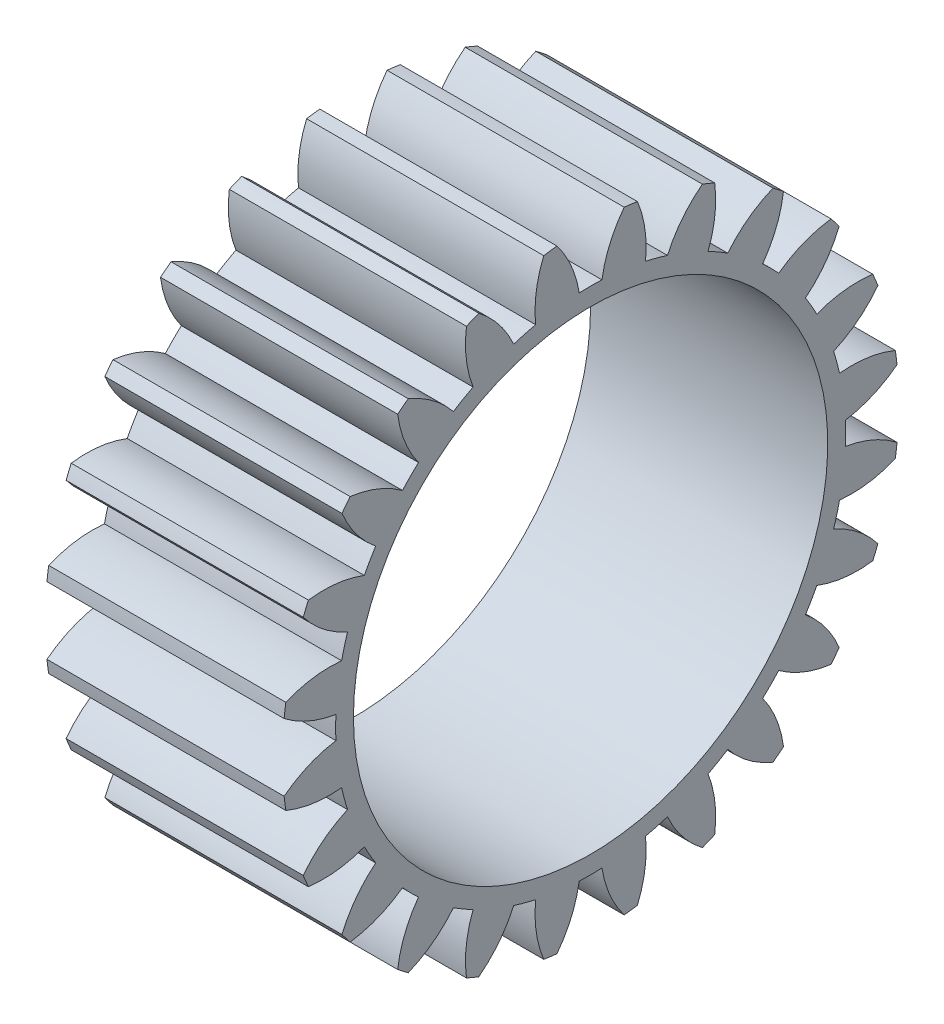
SolidWorks part; units mm, degrees
ref_plane "Plane1" through (0, 0, 0) normal (0, 0, 1) x (1, 0, 0)
ref_plane "Plane2" through (0, 0, 0) normal (0, 1, 0) x (1, 0, 0)
ref_plane "Plane3" through (0, 0, 0) normal (1, 0, 0) x (0, 0, -1)
sketch "HoldingSke" plane through (0, 0, 0) normal (0, 1, 0) x (1, 0, 0)
  line L0 (0, 0) -> (0.609, -0.2712)
  line L1 (-15, 0) -> (100, 0) construction
  line L2 (0, 0) -> (-2.1039, 2.3779)
  line L3 (0, 0) -> (-11.863, 4.5341)
  line L4 (0, 0) -> (7.8894, 3.5126)
  line L5 (0, 0) -> (-46.8476, -17.4728)
  line L6 (0, 0) -> (-12.4344, -8.3896)
  line L7 (-2.1039, 2.3779) -> (8.6586, 51.2059)
  line L8 (-76.2, 54.61) -> (-72.9, 54.61)
  line L9 (-71.009, 38.7566) -> (-53.1078, 45.2721)
  line L10 (-76.2, 71.12) -> (104.1128, 71.12)
  line L11 (0, 0) -> (-15, 0)
  line L12 (-76.2, 101.6) -> (-76.147, 101.6)
  line L13 (24.9733, 27.94) -> (52.9518, 28.4284)
  line L14 (24.9733, 27.94) -> (24.9743, 27.94)
  line L15 (24.9733, 27.94) -> (100.4006, 29.5858)
  line L16 (-63.627, -1.5) -> (-12.827, -1.5)
  circle A0 centre (0, 0) radius 15
  circle A1 centre (0, 0) radius 16.124
  circle A2 centre (0, 0) radius 37.5
  circle A3 centre (0, 0) radius 15
  dimension "MHD" = 32.248
  dimension "Hub_dia" = 75
  dimension "Bore" = 30
  dimension "MBD" = 30
  dimension "Num_teeth" = 24
  dimension "Pitch" = 0.6667
  dimension "Overall_len" = 50
  dimension "Show_teeth" = 24
  dimension "Thickness" = 15
  dimension "OAL" = 50.0001
  dimension "T_dim" = 3.3
  dimension "Ap" = 20
  dimension "H" = 19.05
  dimension "Pitch_radius" = 180.3128
  dimension "Width" = 15
  dimension "Backlash" = 0.053
  dimension "Addendum_fac" = 1
  dimension "Dedendum_fac" = 1.25
  dimension "Clearance_fac" = 0.25
  dimension "Dedendum_add" = 0.001
  dimension "Module" = 1.5
sketch "BasProSke" plane through (0, 0, 0) normal (0, 1, 0) x (1, 0, 0)
  line L0 (-10, 0) -> (60, 0) construction
  line L1 (0, 0) -> (0, 19.5)
  line L2 (0, 0) -> (15, 0)
  line L3 (15, 0) -> (15, 19.5)
  line L4 (15, 19.5) -> (0, 19.5)
  dimension "Thickness" = 15
  dimension "Diameter" = 39
revolve "Base-Revolve" add sketch "BasProSke" angle 360 about L0
sketch "TooCutSke" plane through (0, 0, 0) normal (1, 0, 0) x (0, 0, -1)
  line L1 (0, 0) -> (0, 107) construction
  line L2 (0, 0) -> (-1.27, 17.9551) construction
  line L3 (0, 0) -> (-4.6904, 35.6272) construction
  line L4 (-1.27, 17.9551) -> (-2.3452, 17.8136) construction
  arc A0 (0.719, 16.108) -> (-0.719, 16.108) centre (0, 0) ccw
  arc A1 (2.1447, 19.4073) -> (-2.1447, 19.4073) centre (0, 0) ccw
  circle A2 centre (0, 0) radius 18 construction
  circle A3 centre (0, 0) radius 16.9145 construction
  arc A4 (-0.719, 16.108) -> (-2.1447, 19.4073) centre (-7.832, 14.992) ccw
  arc A5 (2.1447, 19.4073) -> (0.719, 16.108) centre (7.832, 14.992) ccw
  dimension "Root_dia" = 32.248
  dimension "Overcut_dia" = 39.0508
  dimension "Pitch_dia" = 36
  dimension "Base_dia" = 33.8289
  dimension "Flank_rad" = 7.2
  dimension "Half_ang" = 7.5
  dimension "Half_CT" = 1.0845
extrude "ToothCut" cut sketch "TooCutSke" along normal through all
fillet "Breaks" [suppressed] radius 0.03
fillet "RootFillets" [suppressed] radius 0.376
pattern_circular "TeethCuts" count 24 every 15 about axis through (-10, 0, 0) along (1, 0, 0) of "ToothCut", "RootFillets", "Breaks"
sketch "HubNeaOneSke" plane through (0, 0, 0) normal (-1, 0, 0) x (0, 0, 1)
  circle A0 centre (0, 0) radius 16.124
  dimension "Diameter" = 32.248
extrude "HubNearOne" [suppressed] add sketch "HubNeaOneSke" along normal blind 35.0001
sketch "HubNeaBotSke" plane through (0, 0, 0) normal (-1, 0, 0) x (0, 0, 1)
  circle A0 centre (0, 0) radius 16.124
  dimension "Diameter" = 32.248
extrude "HubNearBoth" [suppressed] add sketch "HubNeaBotSke" along normal blind 17.5
ref_plane "FarPln" through (15, 0, 0) normal (1, 0, 0) x (0, 0, -1)
sketch "HubFarSke" plane through (15, 0, 0) normal (1, 0, 0) x (0, 0, -1)
  circle A0 centre (0, 0) radius 16.124
  dimension "Diameter" = 32.248
extrude "HubFar" [suppressed] add sketch "HubFarSke" along normal blind 17.5
sketch "BorSke" plane through (0, 0, 0) normal (1, 0, 0) x (0, 0, -1)
  circle A0 centre (0, 0) radius 15
  dimension "Diameter" = 30
extrude "Bore" cut sketch "BorSke" along normal mid plane 100.0001
sketch "KeySke" plane through (0, 0, 0) normal (1, 0, 0) x (0, 0, -1)
  line L0 (-5, 0) -> (-5, 18.3)
  line L1 (-5, 18.3) -> (5, 18.3)
  line L2 (5, 18.3) -> (5, 0)
  line L3 (0, 0) -> (0, 34) construction
  line L4 (-5, 0) -> (5, 0)
  dimension "Offset" = 18.3
  dimension "Width" = 10
extrude "Keyway" [suppressed] cut sketch "KeySke" along normal mid plane 100.0001
pattern_circular "Keyway2" [suppressed] count 2 every 90 about axis through (-10, 0, 0) along (1, 0, 0)
equation "' \"Module@HoldingSke\" = 6.35"
equation "' \"Num_teeth@HoldingSke\" = 12"
equation "' \"Ap@HoldingSke\" =  20"
equation "' \"Ap@HoldingSke\" = 20"
equation "' \"Width@HoldingSke\" = 0.5 * 25.4"
equation "' \"Hub_dia@HoldingSke\"= 1 * 25.4"
equation "' \"Hub_dia@HoldingSke\" = 1 * 25.4"
equation "' \"Overall_len@HoldingSke\" = 1.0 * 25.4"
equation "' \"Bore@HoldingSke\" = 0.75 * 25.4"
equation "' \"T_dim@HoldingSke\" = 0.1 * 25.4"
equation "' \"Width@KeySke\" = 0.25 * 25.4"
equation "' \"Show_teeth@HoldingSke\" = 13"
equation "' \"Backlash@HoldingSke\" = 0.009 * 25.4"
equation "' \"Addendum_fac@HoldingSke\" = 1.0"
equation "' \"Dedendum_fac@HoldingSke\" = 1.25"
equation "' \"Dedendum_add@HoldingSke\" = 0.00005 * 25.4"
equation "' \"Clearance_fac@HoldingSke\" = 0.25"
equation "\"Pitch@HoldingSke\" = 1 / \"Module@HoldingSke\""
equation "\"Overcut_dia@TooCutSke\" = (\"Num_teeth@HoldingSke\" + 2 * \"Addendum_fac@HoldingSke\") / \"Pitch@HoldingSke\" + 0.002 * 25.4"
equation "\"Pitch_dia@TooCutSke\" = \"Num_teeth@HoldingSke\" / \"Pitch@HoldingSke\""
equation "\"Base_dia@TooCutSke\" = \"Num_teeth@HoldingSke\" / \"Pitch@HoldingSke\" * cos((\"Ap@HoldingSke\"  * 3.14159265 / 180))"
equation "\"Root_dia@TooCutSke\" = (\"Num_teeth@HoldingSke\" + 2) / \"Pitch@HoldingSke\" - 2 * (\"Addendum_fac@HoldingSke\" + \"Dedendum_fac@HoldingSke\") / \"Pitch@HoldingSke\" - \"Dedendum_add@HoldingSke\" * 2"
equation "\"Half_ang@TooCutSke\" = 180 / \"Num_teeth@HoldingSke\""
equation "\"Half_CT@TooCutSke\" = \"Num_teeth@HoldingSke\" / \"Pitch@HoldingSke\" * sin((3.14159265 / 2 / \"Num_teeth@HoldingSke\")) / 2 - 7 * \"Backlash@HoldingSke\" / 4"
equation "\"Flank_rad@TooCutSke\" = \"Num_teeth@HoldingSke\" / \"Pitch@HoldingSke\" / 5"
equation "\"Radius@RootFillets\" = \"Clearance_fac@HoldingSke\" / \"Pitch@HoldingSke\" + \"Dedendum_add@HoldingSke\""
equation "\"Break_rad@Breaks\" = 0.02 / \"Pitch@HoldingSke\""
equation "\"Thickness@HoldingSke\" = \"Width@HoldingSke\""
equation "\"OAL@HoldingSke\" = \"Thickness@HoldingSke\""
equation "\"MHD@HoldingSke\" = (\"Num_teeth@HoldingSke\" + 2) / \"Pitch@HoldingSke\" - 2 * (\"Addendum_fac@HoldingSke\" + \"Dedendum_fac@HoldingSke\")  / \"Pitch@HoldingSke\" - \"Dedendum_add@HoldingSke\" * 2"
equation "\"MBD@HoldingSke\" = (\"Num_teeth@HoldingSke\" + 2) / \"Pitch@HoldingSke\" - 2 * (\"Addendum_fac@HoldingSke\" + \"Dedendum_fac@HoldingSke\")  / \"Pitch@HoldingSke\" - \"Dedendum_add@HoldingSke\" * 2 - 0.002 * 25.4"
equation "\"MHD@HoldingSke\" = ((sgn( \"MHD@HoldingSke\" - \"Hub_dia@HoldingSke\" )-1)*( \"MHD@HoldingSke\" - \"Hub_dia@HoldingSke\" ))/-2+ \"Hub_dia@HoldingSke\""
equation "\"MBD@HoldingSke\" = ((sgn( \"MBD@HoldingSke\" - \"Bore@HoldingSke\" )-1)*( \"MBD@HoldingSke\" - \"Bore@HoldingSke\" ))/-2+ \"Bore@HoldingSke\""
equation "\"OAL@HoldingSke\" = ((sgn( \"OAL@HoldingSke\" - \"Overall_len@HoldingSke\" )+1)*( \"OAL@HoldingSke\" - \"Overall_len@HoldingSke\" ))/2 + \"Overall_len@HoldingSke\" + 0.000002 * 25.4"
equation "\"Num_teeth@TeethCuts\" = int( \"Show_teeth@HoldingSke\" ) + 1"
equation "\"Num_teeth@TeethCuts\" = ((sgn( \"Num_teeth@TeethCuts\" - \"Num_teeth@HoldingSke\" )-1)*( \"Num_teeth@TeethCuts\" - \"Num_teeth@HoldingSke\" ))/-2+ \"Num_teeth@HoldingSke\""
equation "\"Num_teeth@TeethCuts\" = ((sgn( \"Num_teeth@TeethCuts\" - 2.0)+1)*( \"Num_teeth@TeethCuts\" - 2.0))/2 +2.0"
equation "\"Angle@TeethCuts\" = 360.0 / \"Num_teeth@HoldingSke\""
equation "\"Diameter@BasProSke\" = (\"Num_teeth@HoldingSke\" + 2 * \"Addendum_fac@HoldingSke\") / \"Pitch@HoldingSke\""
equation "\"Thickness@BasProSke\"  = \"Thickness@HoldingSke\""
equation "' \"Fillet_rad@BasProSke\" =  \"Thickness@HoldingSke\" * 0.05"
equation "' \"Fillet_rad@BasProSke\" = \"Thickness@HoldingSke\" * 0.05"
equation "\"MHD@HoldingSke\" = ((sgn( \"MHD@HoldingSke\" - \"Root_dia@TooCutSke\" )-1)*( \"MHD@HoldingSke\" - \"Root_dia@TooCutSke\" ))/-2+ \"Root_dia@TooCutSke\""
equation "\"Diameter@HubNeaOneSke\" = \"MHD@HoldingSke\""
equation "\"Length@HubNearOne\" = \"OAL@HoldingSke\" - \"Thickness@BasProSke\""
equation "\"Diameter@HubNeaBotSke\" = \"MHD@HoldingSke\""
equation "\"Length@HubNearBoth\" = ( \"OAL@HoldingSke\" - \"Thickness@BasProSke\" ) / 2.0"
equation "\"Thickness@FarPln\" = \"Thickness@BasProSke\""
equation "\"Diameter@HubFarSke\" = \"MHD@HoldingSke\""
equation "\"Length@HubFar\" = ( \"OAL@HoldingSke\" - \"Thickness@BasProSke\" ) / 2.0"
equation "\"Diameter@BorSke\" = \"MBD@HoldingSke\""
equation "\"D1@Bore\" = \"OAL@HoldingSke\" * 2.0"
equation "\"D1@Keyway\" = \"OAL@HoldingSke\" * 2.0"
equation "\"Offset@KeySke\" = \"T_dim@HoldingSke\" + \"MBD@HoldingSke\" / 2.0"
